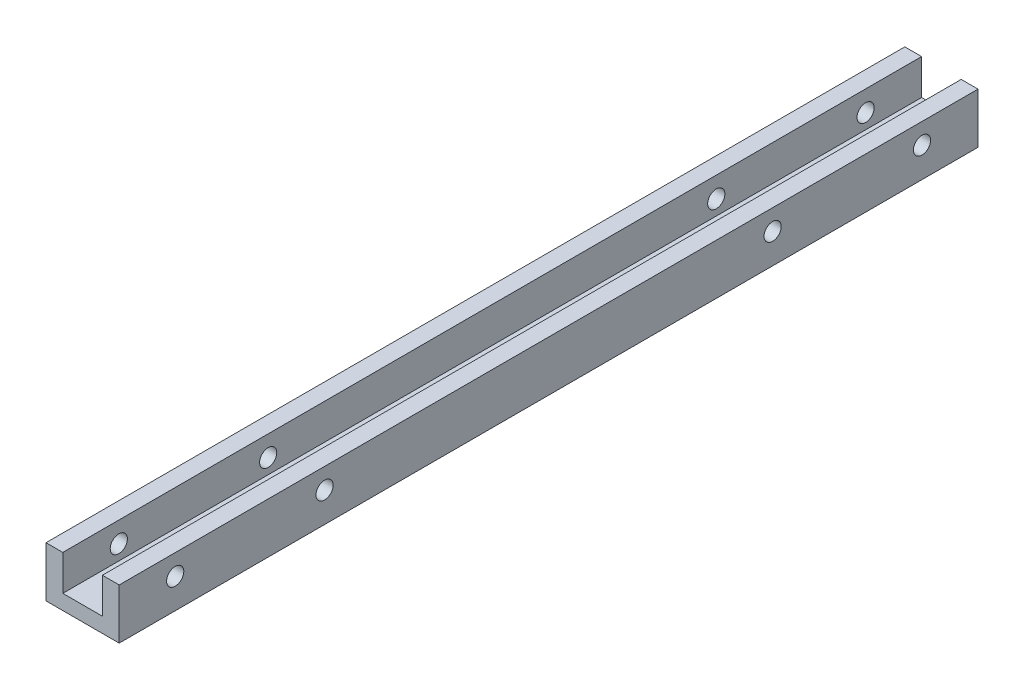
SolidWorks part; units mm, degrees
ref_plane "Спереди" through (0, 0, 0) normal (0, 0, 1) x (1, 0, 0)
ref_plane "Сверху" through (0, 0, 0) normal (0, 1, 0) x (1, 0, 0)
ref_plane "Справа" through (0, 0, 0) normal (1, 0, 0) x (0, 0, -1)
sketch "Эскиз1" plane through (0, 0, 0) normal (0, 0, 1) x (1, 0, 0)
  line L0 (0, 0) -> (0, 9.5)
  line L1 (0, 0) -> (10.6, 0)
  line L2 (10.6, 0) -> (10.6, 9.5)
  line L3 (10.6, 9.5) -> (15.1, 9.5)
  line L4 (15.1, 9.5) -> (15.1, -4)
  line L5 (15.1, -4) -> (-4.5, -4)
  line L6 (-4.5, -4) -> (-4.5, 9.5)
  line L7 (-4.5, 9.5) -> (0, 9.5)
  dimension "D1" = 9.5
  dimension "D2" = 10.6
  dimension "D3" = 4.5
  dimension "D4" = 4
extrude "Бобышка-Вытянуть1" add sketch "Эскиз1" along normal blind 230
sketch "Эскиз2" plane through (15.1, 0, 0) normal (1, 0, 0) x (0, 0, -1)
  line L0 (-215, 4) -> (-175, 4) construction
  line L1 (-175, 4) -> (-135, 4) construction
  line L2 (-135, 4) -> (-95, 4) construction
  line L3 (-95, 4) -> (-55, 4) construction
  line L4 (-55, 4) -> (-15, 4) construction
  circle A0 centre (-215, 4) radius 2.3
  circle A1 centre (-175, 4) radius 2.3
  circle A4 centre (-55, 4) radius 2.3
  circle A5 centre (-15, 4) radius 2.3
  dimension "D1" = 4.6
  dimension "D2" = 4
extrude "Вырез-Вытянуть1" cut sketch "Эскиз2" against normal blind 230
